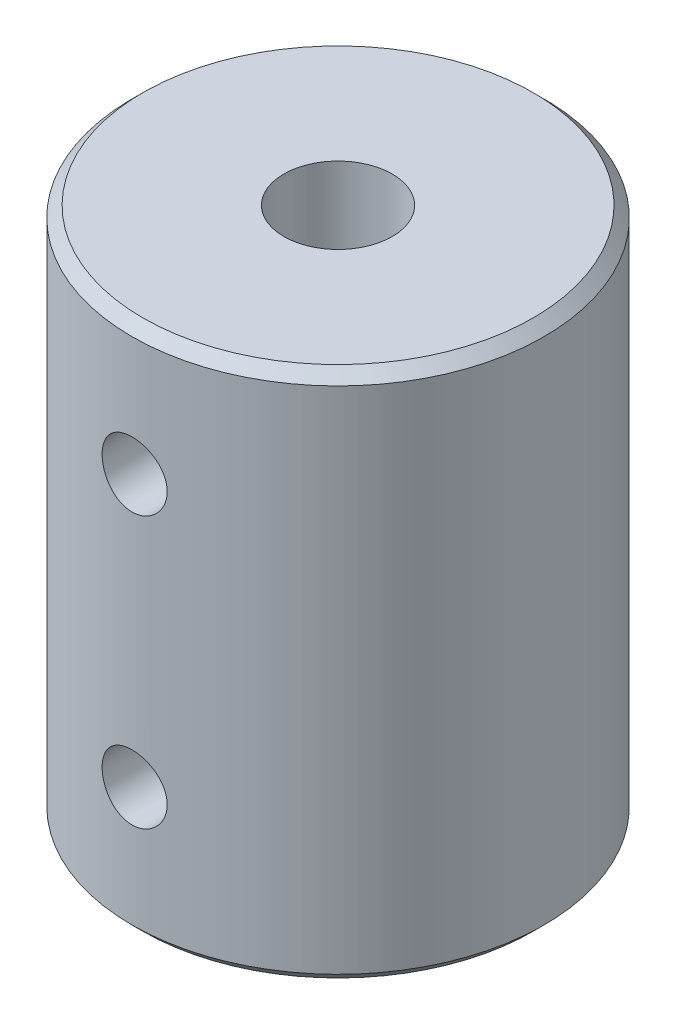
SolidWorks part; units mm, degrees
ref_plane "前视基准面" through (0, 0, 0) normal (0, 0, 1) x (1, 0, 0)
ref_plane "上视基准面" through (0, 0, 0) normal (0, 1, 0) x (1, 0, 0)
ref_plane "右视基准面" through (0, 0, 0) normal (1, 0, 0) x (0, 0, -1)
sketch "草图1" plane through (0, 0, 0) normal (0, 1, 0) x (1, 0, 0)
  circle A0 centre (0, 0) radius 9.5
  circle A1 centre (0, 0) radius 2.5
  dimension "D1" = 19
  dimension "D2" = 5
extrude "凸台-拉伸1" add sketch "草图1" along normal blind 24.5
chamfer "倒角1" distance 0.5 angle 45 2 edges at (0, 0, 9.5) (0, 24.5, 9.5)
sketch "草图2" plane through (0, 0, 0) normal (0, -1, 0) x (1, 0, 0)
  circle A0 centre (0, 0) radius 4
  dimension "D1" = 8
extrude "切除-拉伸1" cut sketch "草图2" against normal blind 10
ref_plane "基准面1" through (0, 0, 9.5) normal (0, 0, 1) x (1, 0, 0)
sketch "草图3" plane through (0, 0, 9.5) normal (0, 0, 1) x (1, 0, 0)
  circle A0 centre (0, 6) radius 1.5
  circle A1 centre (0, 18.5) radius 1.5
extrude "切除-拉伸2" cut sketch "草图3" against normal blind 10
